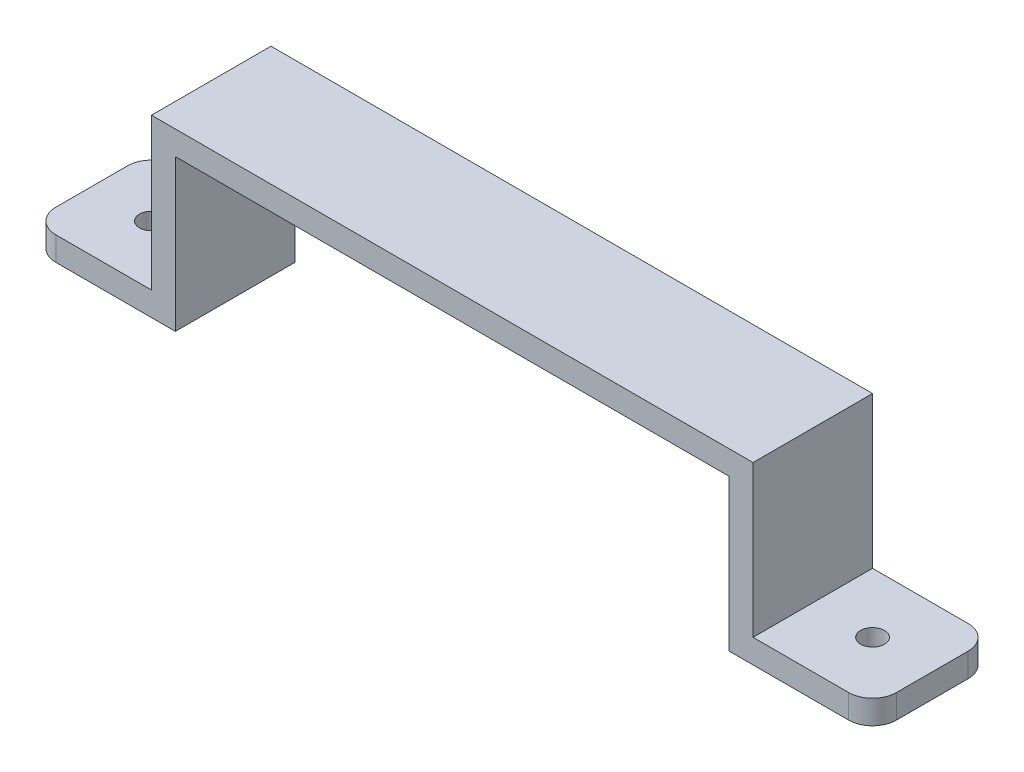
SolidWorks part; units mm, degrees
ref_plane "前视基准面" through (0, 0, 0) normal (0, 0, 1) x (1, 0, 0)
ref_plane "上视基准面" through (0, 0, 0) normal (0, 1, 0) x (1, 0, 0)
ref_plane "右视基准面" through (0, 0, 0) normal (1, 0, 0) x (0, 0, -1)
other "Configuration Table"
sketch "草图1" plane through (0, 0, 0) normal (0, 0, 1) x (1, 0, 0)
  line L0 (-37.75, 0) -> (37.75, 0)
  line L1 (37.75, 0) -> (37.75, -19)
  line L2 (37.75, -19) -> (52.75, -19)
  line L3 (52.75, -19) -> (52.75, -22)
  line L4 (52.75, -22) -> (34.75, -22)
  line L5 (34.75, -22) -> (34.75, -3)
  line L6 (34.75, -3) -> (-34.75, -3)
  line L7 (-34.75, -3) -> (-34.75, -22)
  line L8 (-34.75, -22) -> (-52.75, -22)
  line L9 (-52.75, -22) -> (-52.75, -19)
  line L10 (-52.75, -19) -> (-37.75, -19)
  line L11 (-37.75, -19) -> (-37.75, 0)
  line L12 (0, 0) -> (0, -25.8281) construction
  dimension "D1" = 3
  dimension "D2" = 3
  dimension "D3" = 3
  dimension "D4" = 69.5
  dimension "D5" = 19
  dimension "D6" = 15
extrude "凸台-拉伸1" add sketch "草图1" along normal blind 15
sketch "草图2" plane through (0, -19, 0) normal (0, 1, 0) x (1, 0, 0)
  line L0 (52.75, -15) -> (52.75, 0) construction
  line L1 (-52.75, -15) -> (-52.75, 0) construction
  line L2 (-37.75, 0) -> (-52.75, 0) construction
  line L3 (52.75, 0) -> (37.75, 0) construction
  circle A0 centre (-45.25, -7.5) radius 1.5
  circle A1 centre (45.25, -7.5) radius 1.5
  dimension "D3" = 3
  dimension "D1" = 7.5
  dimension "D2" = 7.5
  dimension "D4" = 7.5
  dimension "D5" = 7.5
extrude "切除-拉伸1" cut sketch "草图2" against normal blind 20
fillet "圆角1" radius 3 4 edges at (-52.75, -20.5, 15) (-52.75, -20.5, 0) (52.75, -20.5, 15) (52.75, -20.5, 0)
